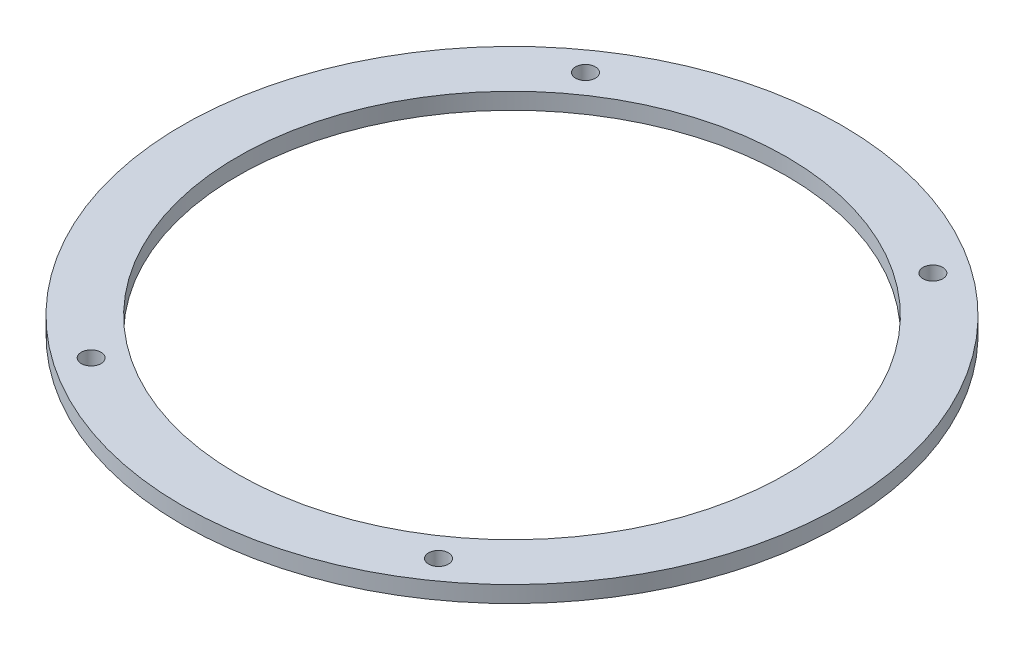
SolidWorks part; units mm, degrees
material "5052-O"
ref_plane "正面" through (0, 0, 0) normal (0, 0, 1) x (1, 0, 0)
ref_plane "平面" through (0, 0, 0) normal (0, 1, 0) x (1, 0, 0)
ref_plane "右側面" through (0, 0, 0) normal (1, 0, 0) x (0, 0, -1)
sketch "ｽｹｯﾁ2" plane through (0, 0, 0) normal (0, 1, 0) x (1, 0, 0)
  circle A0 centre (0, 0) radius 50
  circle A1 centre (0, 0) radius 60
  dimension "D1" = 100
  dimension "D2" = 120
extrude "ﾎﾞｽ - 押し出し2" add sketch "ｽｹｯﾁ2" along normal blind 3
sketch "ｽｹｯﾁ3" plane through (0, 3, 0) normal (0, 1, 0) x (1, 0, 0)
  circle A0 centre (-31.6228, 45) radius 1.5
  circle A1 centre (31.6228, 45) radius 1.5
  dimension "D3" = 3
  dimension "D4" = 3
  dimension "D1" = 55
  dimension "D2" = 55
  dimension "D5" = 45
  dimension "D6" = 45
hole_wizard "M3 Hub_Boardへの固定用穴" positions "3Dｽｹｯﾁ1" profile "ｽｹｯﾁ4" hole size "M3" standard "ISO" end condition through all
sketch3d "3Dｽｹｯﾁ1"
  point P0 (-31.6228, 3, -45)
  point P3 (31.6228, 3, -45)
sketch "ｽｹｯﾁ4" plane through (-31.6228, 3, -45) normal (1, 0, 0) x (0, 0, 1)
  line L0 (0, 0) -> (0, 3)
  line L1 (0, 3) -> (1.8, 3)
  line L2 (1.8, 3) -> (1.8, 0)
  line L5 (1.8, 0) -> (0, 0)
  line L11 (0, -6.35) -> (0, 107.95) construction
  dimension "通し穴の直径" = 3.6
  dimension "通し穴の深さ" = 3
mirror "ﾐﾗｰ1" about plane through (0, 0, 0) normal (0, 0, 1) of "M3 Hub_Boardへの固定用穴"
